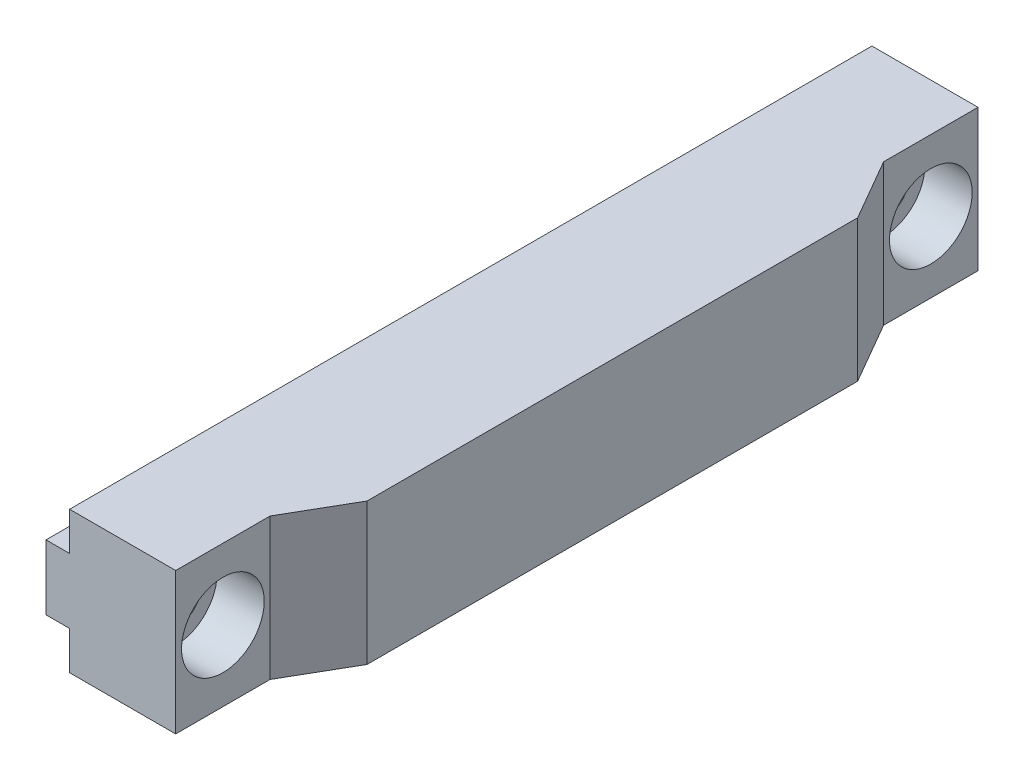
SolidWorks part; units mm, degrees
ref_plane "Front Plane" through (0, 0, 0) normal (0, 0, 1) x (1, 0, 0)
ref_plane "Top Plane" through (0, 0, 0) normal (0, 1, 0) x (1, 0, 0)
ref_plane "Right Plane" through (0, 0, 0) normal (1, 0, 0) x (0, 0, -1)
sketch "Sketch1" plane through (0, 0, 0) normal (0, 1, 0) x (1, 0, 0)
  line L0 (-9.525, -53.975) -> (-9.525, 53.975)
  line L1 (-9.525, 53.975) -> (4.7498, 53.975)
  line L2 (4.7498, 53.975) -> (4.7498, 41.275)
  line L3 (4.7498, 41.275) -> (9.525, 33.0041)
  line L4 (9.525, 33.0041) -> (9.525, -33.0041)
  line L5 (9.525, -33.0041) -> (4.7498, -41.275)
  line L6 (4.7498, -41.275) -> (4.7498, -53.975)
  line L7 (4.7498, -53.975) -> (-9.525, -53.975)
  point P8 (0, 0)
  dimension "D1" = 4.7752
  dimension "D2" = 19.05
  dimension "D3" = 12.7
  dimension "D4" = 20.9709
  dimension "D5" = 86.9791
  dimension "D6" = 95.25
  dimension "D7" = 107.95
  dimension "D8" = 9.525
  dimension "D9" = 53.975
extrude "Boss-Extrude1" add sketch "Sketch1" along normal mid plane 19.05
sketch "Sketch2" plane through (0, 0, 0) normal (1, 0, 0) x (0, 0, -1)
  line L0 (53.975, 9.525) -> (53.975, -9.525) construction
  line L1 (-53.975, -4.3688) -> (53.975, -4.3688)
  line L2 (-53.975, -4.3688) -> (-53.975, 4.3688)
  line L3 (-53.975, 4.3688) -> (53.975, 4.3688)
  line L4 (53.975, -4.3688) -> (53.975, 4.3688)
  line L5 (-53.975, -4.3688) -> (53.975, 4.3688) construction
  line L6 (-53.975, 4.3688) -> (53.975, -4.3688) construction
  point P0 (0, 0)
  dimension "D1" = 4.3688
extrude "Boss-Extrude2" add sketch "Sketch2" along normal blind 3.175 from offset 12.7
sketch "Sketch3" plane through (0, 0, 0) normal (1, 0, 0) x (0, 0, -1)
  circle A0 centre (-47.625, 0) radius 3.5687
  circle A1 centre (47.625, 0) radius 3.5687
  point P4 (0, 0)
  dimension "D1" = 7.1374
  dimension "D2" = 7.1374
  dimension "D3" = 95.25
  dimension "D4" = 47.625
extrude "Cut-Extrude2" cut sketch "Sketch3" against normal blind 22.225 from offset 4.7498
sketch "Sketch4" plane through (0, 0, 0) normal (1, 0, 0) x (0, 0, -1)
  circle A0 centre (-47.625, 0) radius 5.5626
  circle A1 centre (47.625, 0) radius 5.5626
  point P4 (0, 0)
  dimension "D1" = 11.1252
  dimension "D2" = 11.1252
  dimension "D3" = 95.25
  dimension "D4" = 47.625
extrude "Cut-Extrude4" cut sketch "Sketch4" against normal blind 6.35 from offset 4.7498
